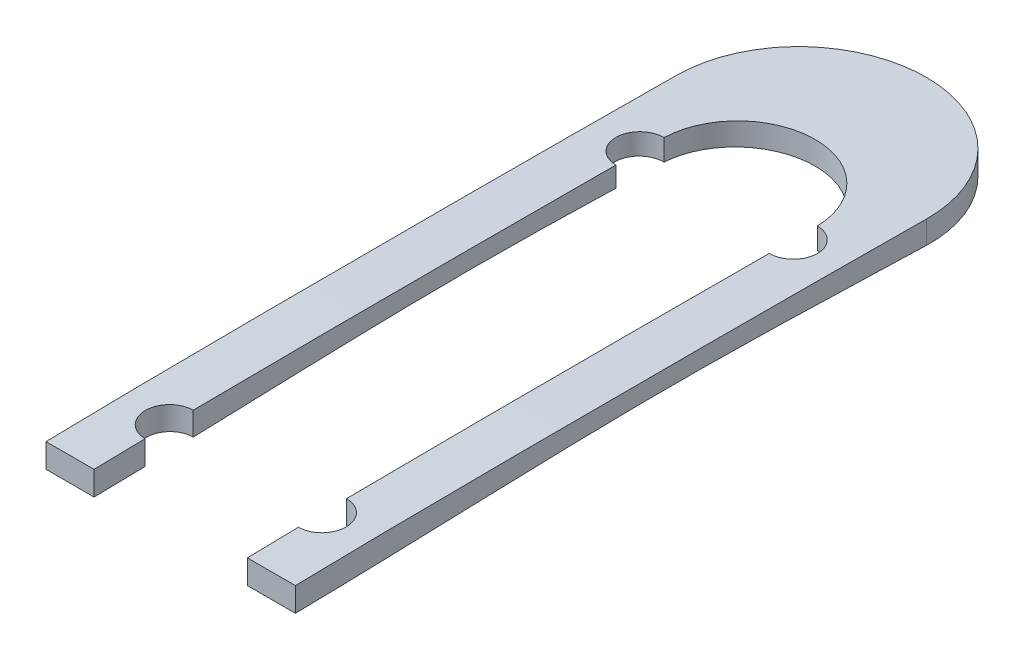
SolidWorks part; units mm, degrees
ref_plane "Front Plane" through (0, 0, 0) normal (0, 0, 1) x (1, 0, 0)
ref_plane "Top Plane" through (0, 0, 0) normal (0, 1, 0) x (1, 0, 0)
ref_plane "Right Plane" through (0, 0, 0) normal (1, 0, 0) x (0, 0, -1)
sketch "Sketch1" plane through (0, 0, 0) normal (0, 1, 0) x (1, 0, 0)
  line L19 (-12.75, 0) -> (-12.75, 8.5027)
  line L21 (0, 0) -> (0, 107.25) construction
  line L22 (12.75, 86.85) -> (12.75, 16.5027)
  line L23 (-12.75, 16.5027) -> (-12.75, 86.85)
  line L24 (12.75, 8.5027) -> (12.75, 0)
  line L25 (-12.75, 0) -> (-20.75, 0)
  line L26 (-20.75, 0) -> (-20.75, 105)
  line L29 (20.75, 105) -> (20.75, 0)
  line L30 (20.75, 0) -> (12.75, 0)
  arc A16 (12.75, 94.5) -> (-12.75, 94.5) centre (0, 94.5) ccw
  arc A17 (-12.7452, 94.85) -> (-12.75, 86.85) centre (-12.75, 90.85) ccw
  arc A18 (-12.75, 16.5027) -> (-12.75, 8.5027) centre (-12.75, 12.5027) ccw
  arc A19 (12.75, 16.5027) -> (12.75, 8.5027) centre (12.75, 12.5027) cw
  arc A20 (12.7452, 94.85) -> (12.75, 86.85) centre (12.75, 90.85) cw
  arc A21 (20.75, 105) -> (-20.75, 105) centre (0, 105) ccw
  point P12 (0, 0)
  dimension "D4" = 8
  dimension "D2" = 94.5
  dimension "D6" = 8
  dimension "D3" = 3.65
  dimension "D1" = 25.5
  dimension "D5" = 12.5027
  dimension "D7" = 105
extrude "Boss-Extrude2" add sketch "Sketch1" along normal blind 10 contours L29 A21 L26 L25 L19 A18 L23 A17 A16 A20 L22 A19 L24 L30
sketch "Sketch2" plane through (20.75, 0, 0) normal (1, 0, 0) x (0, 0, -1)
  line L1 (0, 10) -> (0, 0) construction
  line L4 (0, 6) -> (25, 6.6) construction
  line L5 (25, 6.6) -> (62.875, 6.5) construction
  line L6 (62.875, 6.5) -> (100.7987, 6.6) construction
  line L7 (0, 6) -> (0, 10)
  line L8 (100.7987, 6.6) -> (125.7987, 6) construction
  line L9 (0, 10) -> (125.75, 10)
  line L13 (125.75, 10) -> (125.7987, 6)
  spline S0 degree 4 poles (0, 6) (25, 6.6) (62.875, 6.5) (100.7987, 6.6) (125.7987, 6) knots 0 0 0 0 0 1 1 1 1 1
  point P2 (62.875, 10)
  dimension "D5" = 125.8049
  dimension "D1" = 25
  dimension "D2" = 4
  dimension "D3" = 25
  dimension "D4" = 3.4
  dimension "D6" = 3.5
  dimension "D7" = 3.4
extrude "Cut-Extrude1" cut sketch "Sketch2" against normal up to surface (41.5 mm away)
sketch "Sketch3" plane through (20.75, 0, 0) normal (1, 0, 0) x (0, 0, -1)
  line L0 (0, 0) -> (0, 2)
  line L1 (0, 6) -> (0, 0) construction
  line L2 (0, 0) -> (125.75, 0)
  line L3 (125.75, 0) -> (125.75, 2)
  line L4 (125.75, 0) -> (125.75, 6.0012) construction
  spline S0 degree 3 poles (0, 2) (20.9573, 2.3182) (62.875, 4.6818) (104.7927, 2.3182) (125.75, 2) knots 0 0 0 0 0.5 1 1 1 1
  point P5 (0, 0)
  point P12 (62.875, 0)
  dimension "D1" = 2
  dimension "D2" = 20
  dimension "D3" = 20
  dimension "D4" = 2.5
  dimension "D5" = 3.5
  dimension "D6" = 2.5
  dimension "D7" = 2
extrude "Cut-Extrude2" cut sketch "Sketch3" against normal up to surface (41.5 mm away) up to face at (-20.75, 3.0401, -39.375)
